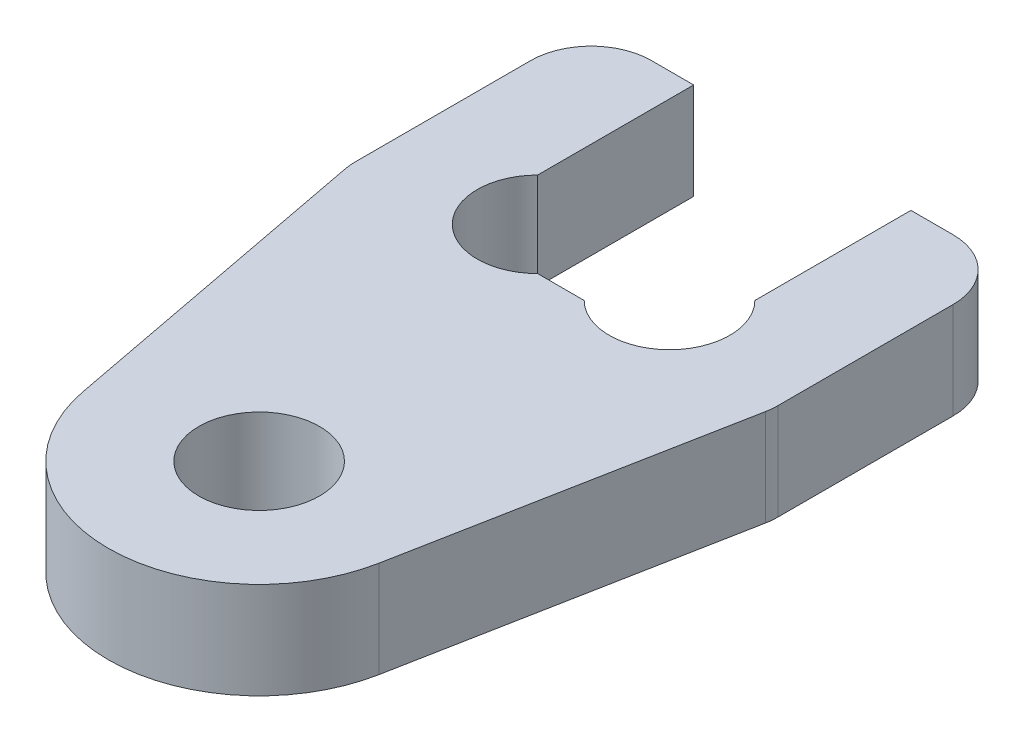
SolidWorks part; units mm, degrees
material "Oshpark board"
ref_plane "Front Plane" through (0, 0, 0) normal (0, 0, 1) x (1, 0, 0)
ref_plane "Top Plane" through (0, 0, 0) normal (0, 1, 0) x (1, 0, 0)
ref_plane "Right Plane" through (0, 0, 0) normal (1, 0, 0) x (0, 0, -1)
sketch "Sketch1" plane through (0, 0, 0) normal (0, 1, 0) x (1, 0, 0)
  line L0 (-3.5, 6) -> (3.5, -6) construction
  line L1 (-3.5, 6) -> (3.5, 6)
  line L2 (-3.5, 6) -> (-3.5, -6)
  line L3 (-3.5, -6) -> (3.5, -6)
  line L4 (3.5, 6) -> (3.5, -6)
  line L5 (0, 6) -> (0, -6) construction
  point P4 (0, 0)
  dimension "D1" = 7
  dimension "D2" = 12
extrude "Boss-Extrude1" add sketch "Sketch1" along normal blind 1.6
sketch "Sketch3" plane through (0, 0, 0) normal (0, -1, 0) x (1, 0, 0)
  line L0 (3.5, -6) -> (-3.5, -6) construction
  line L1 (1.8, -6) -> (-1.8, -6)
  line L2 (1.8, -6) -> (1.8, -2)
  line L3 (1.8, -2) -> (-1.8, -2)
  line L4 (-1.8, -6) -> (-1.8, -2)
  line L5 (1.8, -6) -> (-1.8, -2) construction
  line L6 (1.8, -2) -> (-1.8, -6) construction
  point P4 (0, -4)
  point P7 (0, -6)
  dimension "D1" = 3.6
  dimension "D2" = 4
extrude "Cut-Extrude2" cut sketch "Sketch3" against normal through all
sketch "Sketch4" plane through (0, 1.6, 0) normal (0, 1, 0) x (1, 0, 0)
  line L0 (-3.5, -6) -> (3.5, -6) construction
  circle A0 centre (0, -3) radius 1
  dimension "D1" = 2
  dimension "D2" = 3
extrude "Cut-Extrude3" cut sketch "Sketch4" against normal blind 10
sketch "Sketch5" plane through (0, 1.6, 0) normal (0, 1, 0) x (1, 0, 0)
  line L2 (2.4556, -3.4689) -> (3.5, 2)
  line L3 (3.5, -6) -> (3.5, 6) construction
  line L4 (-2.4556, -3.4689) -> (-3.5, 2)
  line L5 (-3.5, 6) -> (-3.5, -6) construction
  line L6 (1.8, 2) -> (-1.8, 2) construction
  line L7 (3.5, 2) -> (6.1783, -2.3686)
  line L8 (6.1783, -2.3686) -> (0.8013, -12.4368)
  line L9 (0.8013, -12.4368) -> (-8.0527, -5.5)
  line L10 (-8.0527, -5.5) -> (-3.5, 2)
  arc A0 (2.4556, -3.4689) -> (-2.4556, -3.4689) centre (0, -3) cw
  circle A1 centre (0, -3) radius 1 construction
  dimension "D1" = 2.5
extrude "Cut-Extrude4" cut sketch "Sketch5" against normal through all and the other way through all
fillet "Fillet1" radius 1 4 edges at (3.5, 0.8, -6) (-3.5, 0.8, -6) (-3.5, 0.8, -2) (3.5, 0.8, -2)
sketch "Sketch2" plane through (0, 0, 0) normal (0, -1, 0) x (1, 0, 0)
  line L0 (-1.1068, 5.4814) -> (-1.1068, -5.4972) construction
  text T0 "RBF"
extrude "Cut-Extrude1" [suppressed] cut sketch "Sketch2" against normal blind 0.01
sketch "Sketch8" plane through (0, 1.6, 0) normal (0, 1, 0) x (1, 0, 0)
  line L0 (1.8, 6) -> (1.8, 2) construction
  line L1 (1.8, 2) -> (-1.8, 2) construction
  line L2 (0, 2) -> (0, 4.4651) construction
  line L3 (1.8, 3.4142) -> (0.3858, 2)
  line L4 (-1.8, 3.4142) -> (-0.3858, 2)
  arc A0 (1.8, 3.4142) -> (0.3858, 2) centre (1.0929, 2.7071) cw
  arc A1 (-1.8, 3.4142) -> (-0.3858, 2) centre (-1.0929, 2.7071) ccw
  point P3 (1.8, 2)
  dimension "D1" = 1
extrude "Cut-Extrude5" cut sketch "Sketch8" against normal through all
